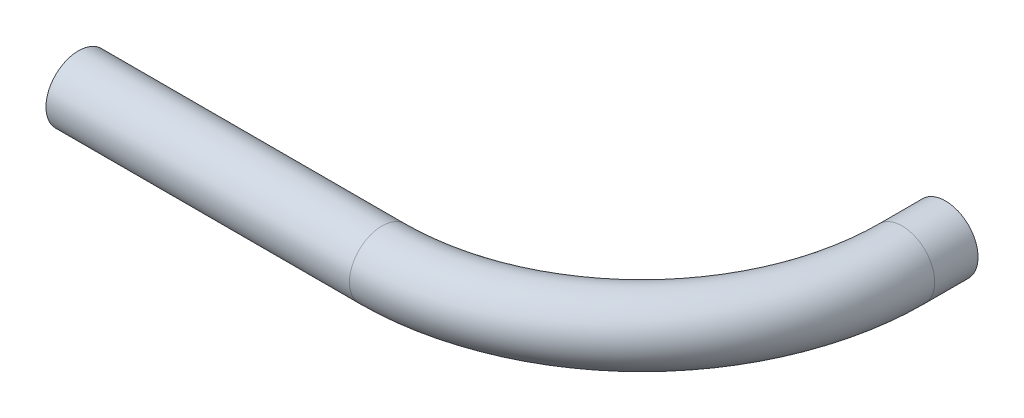
SolidWorks part; units mm, degrees
ref_plane "Front Plane" through (0, 0, 0) normal (0, 0, 1) x (1, 0, 0)
ref_plane "Top Plane" through (0, 0, 0) normal (0, 1, 0) x (1, 0, 0)
ref_plane "Right Plane" through (0, 0, 0) normal (1, 0, 0) x (0, 0, -1)
sketch "Sketch1" plane through (0, 0, 0) normal (0, 1, 0) x (1, 0, 0)
  line L0 (0, 0) -> (177.8, 0)
  line L1 (330.2, 152.4) -> (330.2, 177.8)
  arc A0 (177.8, 0) -> (330.2, 152.4) centre (177.8, 152.4) ccw
  point P6 (330.2, 0)
  dimension "D3" = 152.4
  dimension "D1" = 330.2
  dimension "D2" = 177.8
ref_plane "Plane1" through (0, 0, 0) normal (1, 0, 0) x (0, 0, -1)
sketch "Sketch2" plane through (0, 0, 0) normal (1, 0, 0) x (0, 0, -1)
  circle A0 centre (0, 0) radius 19.05
  circle A1 centre (0, 0) radius 17.399
  dimension "D1" = 38.1
  dimension "D2" = 1.651
sweep "Sweep1" add profiles "Sketch2" path "Sketch1"
